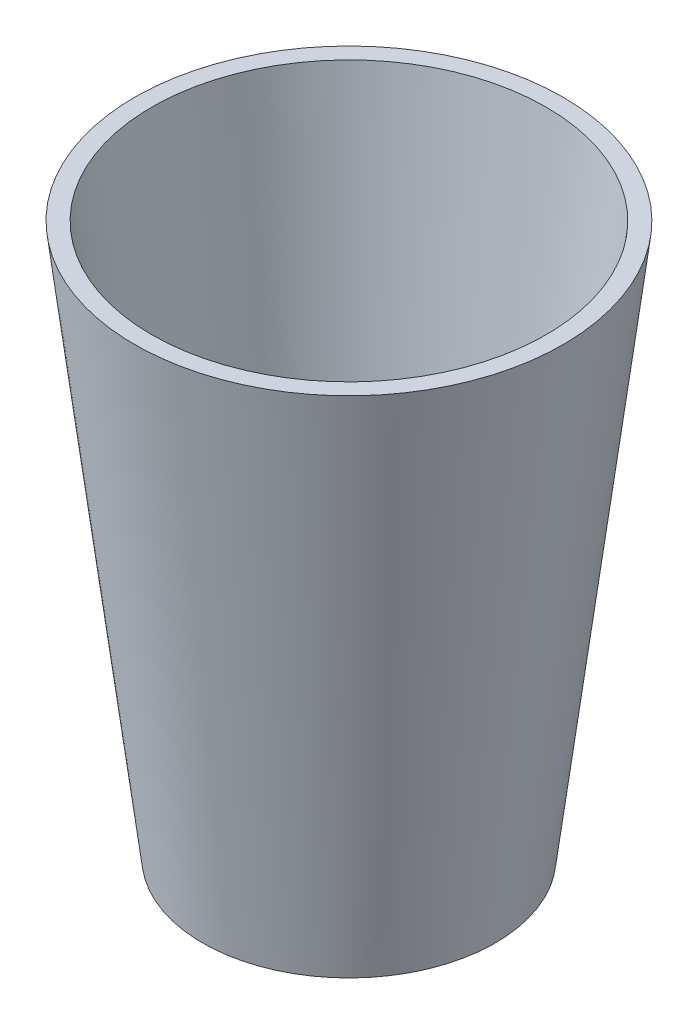
SolidWorks part; units mm, degrees
ref_plane "前视基准面" through (0, 0, 0) normal (0, 0, 1) x (1, 0, 0)
ref_plane "上视基准面" through (0, 0, 0) normal (0, 1, 0) x (1, 0, 0)
ref_plane "右视基准面" through (0, 0, 0) normal (1, 0, 0) x (0, 0, -1)
other "Configuration Table"
sketch "草图1" plane through (0, 0, 0) normal (0, 0, 1) x (1, 0, 0)
  line L0 (0, 0) -> (0, 50) construction
  dimension "D1" = 50
sketch "草图2" plane through (0, 0, 0) normal (0, 0, 1) x (1, 0, 0)
  line L0 (0, 0) -> (23.3355, 0)
  line L1 (23.3355, 0) -> (35, 95)
  line L2 (35, 95) -> (38.0225, 95)
  line L3 (38.0225, 95) -> (25.9896, -3)
  line L4 (25.9896, -3) -> (0, -3)
  line L5 (0, -3) -> (0, 0)
  line L6 (0, 0) -> (0, 50) construction
  point P3 (12.9948, -3)
  dimension "D1" = 3
  dimension "D2" = 3
  dimension "D3" = 95
  dimension "D4" = 97
  dimension "D5" = 35
revolve "旋转1" add sketch "草图2" angle 360 about L0
